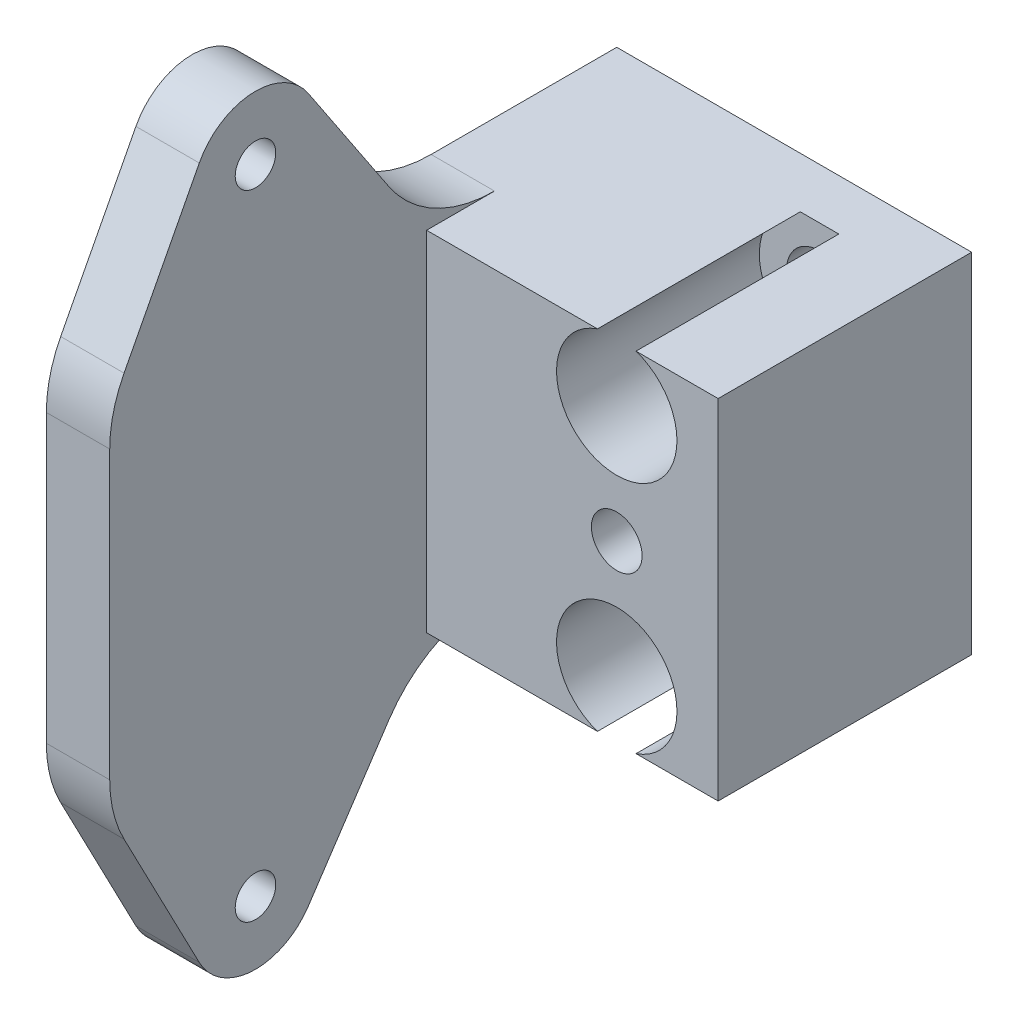
SolidWorks part; units mm, degrees
ref_plane "前视基准面" through (0, 0, 0) normal (0, 0, 1) x (1, 0, 0)
ref_plane "上视基准面" through (0, 0, 0) normal (0, 1, 0) x (1, 0, 0)
ref_plane "右视基准面" through (0, 0, 0) normal (1, 0, 0) x (0, 0, -1)
sketch "草图1" plane through (0, 0, 0) normal (0, 0, 1) x (1, 0, 0)
  line L0 (0, 0) -> (15, 0) construction
  line L1 (8, -13.75) -> (-15, -13.75)
  line L3 (8, 13.75) -> (-15, 13.75)
  line L4 (-15, -13.75) -> (-15, 13.75)
  line L5 (0, 9.25) -> (0, 0) construction
  line L6 (0, 0) -> (0, -9.25) construction
  line L7 (0, 9.25) -> (0, 0) construction
  line L8 (8, 13.75) -> (8, -13.75)
  circle A0 centre (0, 9.25) radius 2.6
  circle A1 centre (0, -9.25) radius 2.6
  circle A2 centre (0, 0) radius 2
  point P0 (0, 0)
  dimension "D1" = 5.2
  dimension "D2" = 18.5
  dimension "D5" = 4
  dimension "D3" = 15
  dimension "D6" = 8
  dimension "D7" = 27.5
extrude "凸台-拉伸1" add sketch "草图1" along normal blind 20
sketch "草图2" plane through (-15, 0, 0) normal (-1, 0, 0) x (0, 0, 1)
  line L0 (0, 13.75) -> (20, 13.75)
  line L1 (45, 13.75) -> (45, -13.75)
  line L3 (0, 13.75) -> (0, -13.75)
  line L4 (20, 13.75) -> (20, -13.75) construction
  line L5 (33.5, 25) -> (33.5, -25) construction
  line L6 (0, 0) -> (33.5, 0) construction
  line L7 (20, 13.75) -> (29.3385, 27.7716)
  line L8 (37.9342, 27.3105) -> (45, 13.75)
  line L9 (37.9342, -27.3105) -> (45, -13.75)
  line L10 (20, -13.75) -> (29.3385, -27.7716)
  line L11 (20, 13.75) -> (45, 13.75) construction
  line L12 (20, -13.75) -> (0, -13.75)
  line L13 (20, -13.75) -> (45, -13.75) construction
  circle A0 centre (33.5, 25) radius 1.6
  circle A1 centre (33.5, -25) radius 1.6
  arc A2 (29.3385, 27.7716) -> (37.9342, 27.3105) centre (33.5, 25) cw
  arc A3 (29.3385, -27.7716) -> (37.9342, -27.3105) centre (33.5, -25) ccw
  dimension "D3" = 3.2
  dimension "D5" = 5
  dimension "D1" = 25
  dimension "D2" = 50
  dimension "D4" = 13.5
sketch "草图3" plane through (0, 0, 20) normal (0, 0, 1) x (1, 0, 0)
  circle A0 centre (0, 9.25) radius 4.75
  circle A1 centre (0, -9.25) radius 4.75
  dimension "D1" = 9.5
extrude "切除-拉伸3" cut sketch "草图3" against normal blind 16
extrude "凸台-拉伸2" add sketch "草图2" along normal blind 5
fillet "圆角1" radius 10 4 edges at (-17.5, -13.75, 20) (-17.5, 13.75, 20) (-17.5, 13.75, 45) (-17.5, -13.75, 45)
